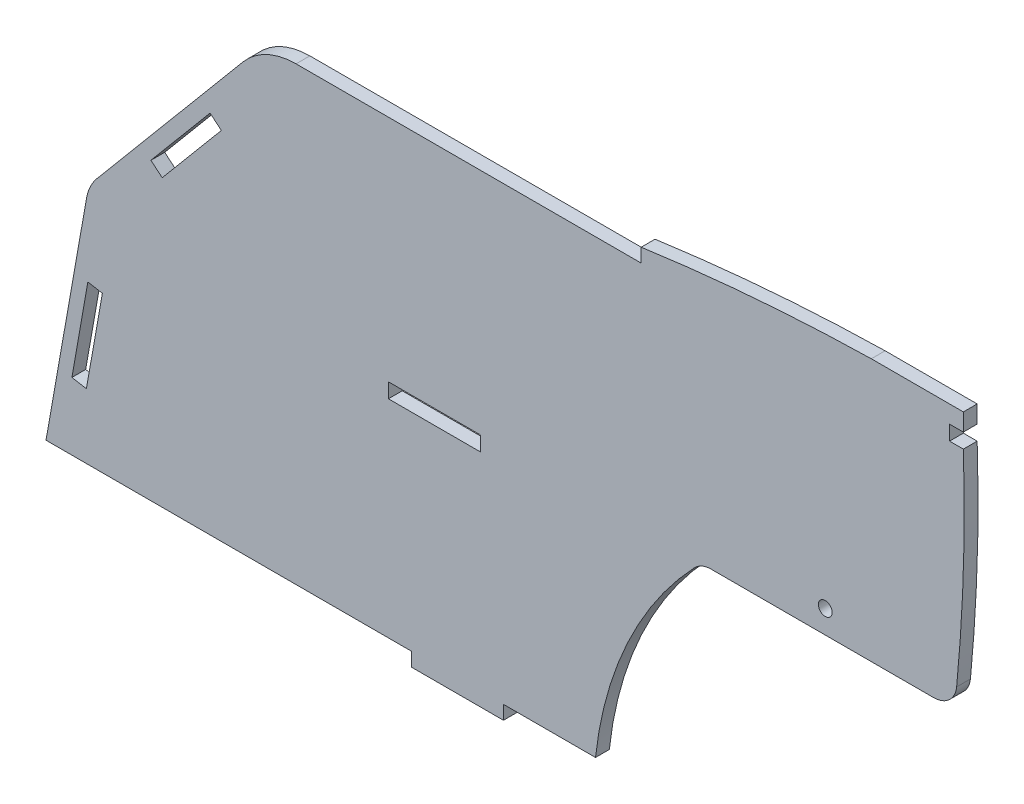
SolidWorks part; units mm, degrees
material "Acrylic (Medium-high impact)"
ref_plane "Front Plane" through (0, 0, 0) normal (0, 0, 1) x (1, 0, 0)
ref_plane "Top Plane" through (0, 0, 0) normal (0, 1, 0) x (1, 0, 0)
ref_plane "Right Plane" through (0, 0, 0) normal (1, 0, 0) x (0, 0, -1)
sketch "Sketch1" plane through (0, 0, 0) normal (0, 0, 1) x (1, 0, 0)
  line L0 (-45.0693, 73) -> (29.9307, 73)
  line L6 (93.4932, 23) -> (45.1087, 23)
  line L13 (-25, 23.2) -> (-5, 23.2)
  line L14 (-25, 23.2) -> (-25, 20)
  line L15 (-25, 20) -> (-5, 20)
  line L16 (-5, 23.2) -> (-5, 20)
  line L17 (-25, 23.2) -> (-5, 20) construction
  line L18 (-25, 20) -> (-5, 23.2) construction
  line L25 (-99.4082, -25) -> (-20, -25)
  line L26 (-20, -25) -> (-20, -27.9999)
  line L27 (-20, -27.9999) -> (0, -27.9999)
  line L28 (0, -27.9999) -> (0, -25)
  line L29 (0, -25) -> (20, -25)
  line L30 (0, 0) -> (-95, 0) construction
  line L31 (-88.4042, 29.6914) -> (-56.56, 67.6418)
  line L32 (-76.6118, 39.0778) -> (-74.1605, 37.0209)
  line L33 (-76.6118, 39.0778) -> (-63.7561, 54.3987)
  line L34 (-74.1605, 37.0209) -> (-61.3047, 52.3418)
  line L35 (-63.7561, 54.3987) -> (-61.3047, 52.3418)
  line L36 (-70.184, 46.7382) -> (-72.4821, 48.6666) construction
  line L38 (-90.5918, 25) -> (-99.4082, -25)
  line L39 (-93.7821, -10.369) -> (-90.3091, 9.3271)
  line L40 (-93.7821, -10.369) -> (-90.6307, -10.9247)
  line L41 (-90.3091, 9.3271) -> (-87.1577, 8.7715)
  line L42 (-90.6307, -10.9247) -> (-87.1577, 8.7715)
  line L43 (-92.0456, -0.5209) -> (-95, 0) construction
  line L44 (99.9307, 80) -> (79.9307, 80)
  line L45 (29.9307, 73) -> (29.9307, 76)
  line L46 (99.9307, 80) -> (99.9307, 73)
  arc A3 (20, -25) -> (41.4802, 21.44) centre (99.5363, -33.6007) cw
  arc A5 (-45.0693, 73) -> (-56.56, 67.6418) centre (-45.0693, 58) ccw
  arc A7 (-88.4042, 29.6914) -> (-90.5918, 25) centre (-80.7437, 23.2635) ccw
  arc A13 (45.1087, 23) -> (41.4802, 21.44) centre (45.1087, 18) ccw
  circle A14 centre (69.9307, 28) radius 1.5
  arc A17 (29.9307, 76) -> (79.9307, 80) centre (88.5237, -341.9125) cw
  arc A20 (98.4697, 27.5149) -> (99.9307, 73) centre (-249.8794, 61.47) ccw
  arc A21 (98.4697, 27.5149) -> (93.4932, 23) centre (93.4932, 28) cw
  point P1 (0, 0)
  point P11 (-15, 21.6)
  point P33 (-95, 0)
  point P38 (-90.1265, 27.6388)
  point P45 (43, 23)
  point P49 (0, 0)
  point P52 (98, 23)
  dimension "D7" = 7
  dimension "D3" = 15
  dimension "D9" = 98
  dimension "D10" = 55
  dimension "D12" = 80
  dimension "D2" = 25
  dimension "D11" = 10
  dimension "D8" = 7
  dimension "D20" = 20
  dimension "D21" = 70
  dimension "D22" = 5
  dimension "D23" = 3
  dimension "D29" = 422
  dimension "D27" = 145
  dimension "D30" = 350
  dimension "D31" = 78
  dimension "D32" = 30
  dimension "D33" = 5
  dimension "D4" = 20
  dimension "D5" = 3.2
  dimension "D6" = 45
  dimension "D13" = 20
  dimension "D14" = 130
  dimension "D15" = 3
  dimension "D16" = 3
  dimension "100" = 95
  dimension "D17" = 280
  dimension "D18" = 15
  dimension "D19" = 20
  dimension "D24" = 48
  dimension "D25" = 2.9999
  dimension "D26" = 5
  dimension "D28" = 3
extrude "Boss-Extrude1" add sketch "Sketch1" along normal blind 3
sketch "Sketch2" plane through (0, 0, 3) normal (0, 0, 1) x (1, 0, 0)
  line L0 (99.9307, 73) -> (99.9307, 80) construction
  line L1 (96.9307, 76.2) -> (99.9307, 76.2)
  line L2 (96.9307, 76.2) -> (96.9307, 73)
  line L3 (96.9307, 73) -> (99.9307, 73)
  line L4 (99.9307, 76.2) -> (99.9307, 73)
  line L5 (96.9307, 76.2) -> (99.9307, 73) construction
  line L6 (96.9307, 73) -> (99.9307, 76.2) construction
  line L10 (29.9307, 73) -> (-45.0693, 73) construction
  point P0 (98.4307, 74.6)
  point P5 (0, 0)
  point P6 (0, 0)
  dimension "D1" = 3.2
  dimension "D2" = 3
extrude "Cut-Extrude1" cut sketch "Sketch2" against normal blind 10
